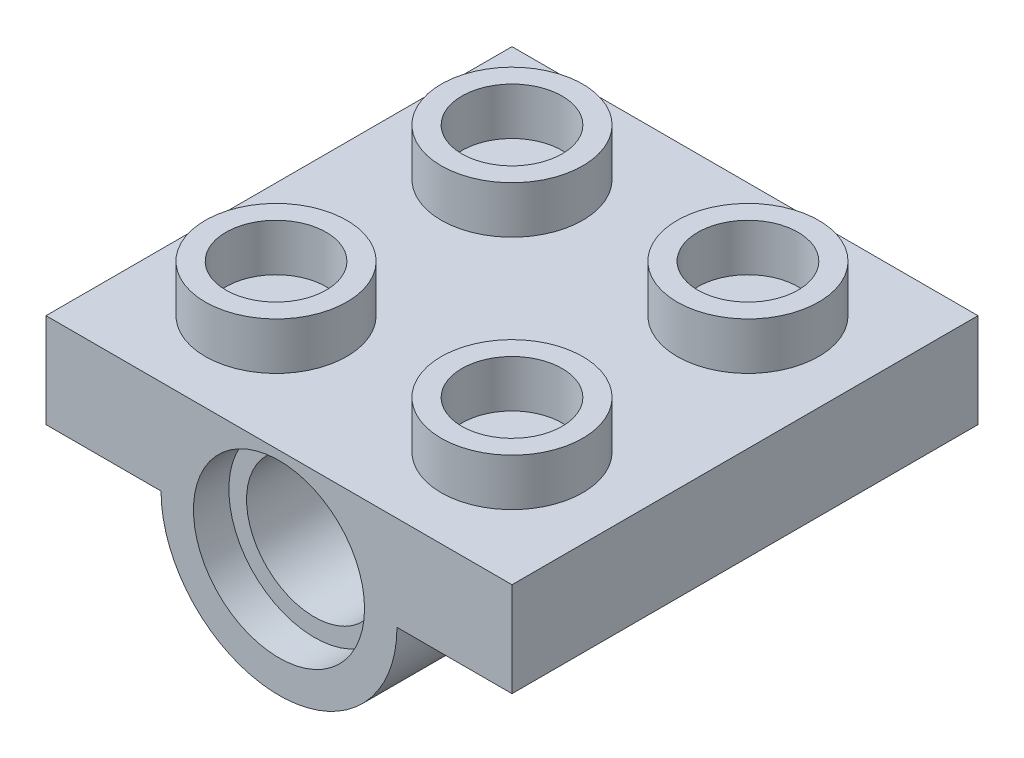
SolidWorks part; units mm, degrees
material "ABS"
ref_plane "Front Plane" through (0, 0, 0) normal (0, 0, 1) x (1, 0, 0)
ref_plane "Top Plane" through (0, 0, 0) normal (0, 1, 0) x (1, 0, 0)
ref_plane "Right Plane" through (0, 0, 0) normal (1, 0, 0) x (0, 0, -1)
sketch "Sketch1" plane through (0, 0, 0) normal (0, 0, 1) x (1, 0, 0)
  line L1 (0, 0) -> (15.8, 0)
  line L2 (0, 0) -> (0, 3.2)
  line L3 (0, 3.2) -> (15.8, 3.2)
  line L4 (15.8, 0) -> (15.8, 3.2)
  line L5 (0, 0) -> (15.8, 3.2) construction
  line L6 (0, 3.2) -> (15.8, 0) construction
  point P4 (7.9, 1.6)
  dimension "D1" = 15.8
  dimension "D2" = 3.2
extrude "Boss-Extrude1" add sketch "Sketch1" against normal blind 15.8
sketch "Sketch2" plane through (0, 3.2, 0) normal (0, 1, 0) x (1, 0, 0)
  line L0 (15.8, 0) -> (0, 0) construction
  circle A0 centre (3.9, 3.9) radius 2.4
  dimension "D1" = 4.8
  dimension "D2" = 3.9
  dimension "D3" = 3.9
extrude "Boss-Extrude2" add sketch "Sketch2" along normal blind 1.6
sketch "Sketch10" plane through (0, 4.8, 0) normal (0, 1, 0) x (1, 0, 0)
  circle A0 centre (3.9, 3.9) radius 1.7
  circle A1 centre (3.9, 3.9) radius 2.4 construction
  dimension "D1" = 0.7
extrude "Cut-Extrude8" cut sketch "Sketch10" against normal up to surface (1.6 mm away) up to face at (3.9, 3.2, -1.5)
pattern_linear "LPattern1" count 2 spacing 8 along (0, 0, -1) count 2 spacing 8 along (1, 0, 0) of "Boss-Extrude2", "Cut-Extrude8"
sketch "Sketch3" plane through (0, 0, 0) normal (0, -1, 0) x (1, 0, 0)
  line L0 (1.2, -1.2) -> (14.6, -1.2)
  line L1 (14.6, -1.2) -> (14.6, -14.6)
  line L2 (14.6, -14.6) -> (1.2, -14.6)
  line L3 (1.2, -14.6) -> (1.2, -1.2)
  line L4 (0, 0) -> (15.8, 0) construction
  line L5 (0, -15.8) -> (0, 0) construction
  line L6 (0, -15.8) -> (15.8, -15.8) construction
  line L7 (15.8, -15.8) -> (15.8, 0) construction
  dimension "D1" = 1.2
  dimension "D2" = 1.2
  dimension "D3" = 1.2
  dimension "D4" = 1.2
extrude "Cut-Extrude1" cut sketch "Sketch3" against normal offset from surface (3 mm away) 0.2 up to face at (11.9, 3.2, -9.5)
sketch "Sketch4" plane through (0, 0, 0) normal (0, 0, 1) x (1, 0, 0)
  line L0 (11.9, 0) -> (11.9, 3.2)
  line L1 (0, 0) -> (15.8, 0) construction
  line L2 (15.8, 3.2) -> (0, 3.2) construction
  line L3 (3.9, 0) -> (3.9, 3.2)
  line L4 (11.9, 3.2) -> (3.9, 3.2)
  arc A0 (11.9, 0) -> (3.9, 0) centre (7.9, 0) cw
  point P10 (7.9, 0)
  dimension "D1" = 8
extrude "Boss-Extrude3" add sketch "Sketch4" against normal blind 6.9
sketch "Sketch8" plane through (0, 0, 0) normal (0, 0, 1) x (1, 0, 0)
  arc A0 (3.9, 0) -> (11.9, 0) centre (7.9, 0) ccw construction
  arc A1 (3.9, 0) -> (11.9, 0) centre (7.9, 0) ccw construction
  circle A2 centre (7.9, 0) radius 2.9
  dimension "D1" = 5.8
extrude "Cut-Extrude6" cut sketch "Sketch8" against normal blind 1.2
sketch "Sketch9" plane through (0, 0, -1.2) normal (0, 0, 1) x (1, 0, 0)
  circle A0 centre (7.9, 0) radius 2.3
  dimension "D1" = 4.6
extrude "Cut-Extrude7" cut sketch "Sketch9" against normal up to surface (5.7 mm away) and the other way through all up to face at (7.9, 0.5, -6.9)
ref_plane "Plane1" through (0, 0, -7.9) normal (0, 0, 1) x (1, 0, 0)
mirror "Mirror1" about plane through (0, 0, -7.9) normal (0, 0, 1) of "Boss-Extrude3", "Cut-Extrude6", "Cut-Extrude7"
